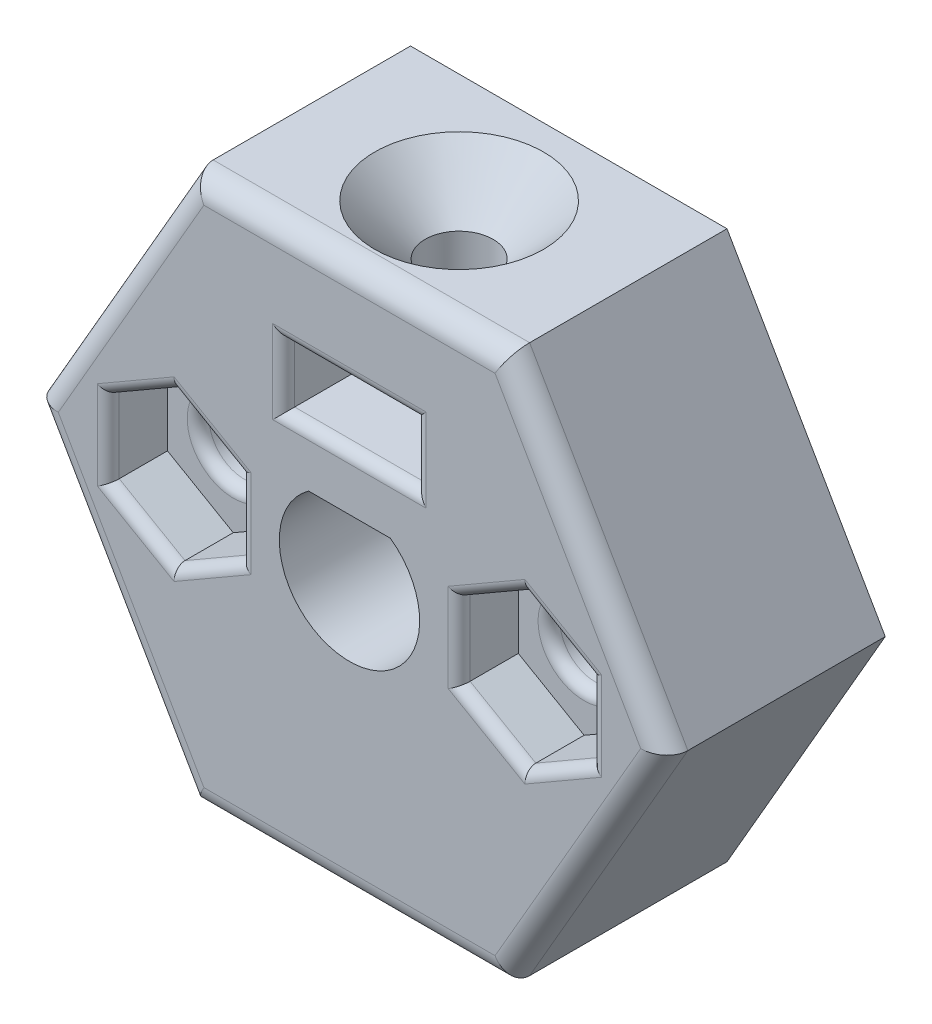
SolidWorks part; units mm, degrees
material "ABS"
ref_plane "Спереди" through (0, 0, 0) normal (0, 0, 1) x (1, 0, 0)
ref_plane "Сверху" through (0, 0, 0) normal (0, 1, 0) x (1, 0, 0)
ref_plane "Справа" through (0, 0, 0) normal (1, 0, 0) x (0, 0, -1)
sketch "Эскиз1" plane through (0, 0, 0) normal (0, 0, 1) x (1, 0, 0)
  line L1 (7.2169, -12.5) -> (14.4338, 0)
  line L2 (14.4338, 0) -> (7.2169, 12.5)
  line L3 (7.2169, 12.5) -> (-7.2169, 12.5)
  line L4 (-7.2169, 12.5) -> (-14.4338, 0)
  line L5 (-14.4338, 0) -> (-7.2169, -12.5)
  line L6 (-7.2169, -12.5) -> (7.2169, -12.5)
  circle A0 centre (0, 0) radius 12.5 construction
  dimension "D1" = 25
extrude "Бобышка-Вытянуть1" add sketch "Эскиз1" along normal blind 10
sketch "Эскиз2" plane through (0, 0, 10) normal (0, 0, 1) x (1, 0, 0)
  line L0 (-1.8, 2.4) -> (1.8, 2.4) construction
  line L1 (0, 2.4) -> (0, -3) construction
  line L2 (3, 0) -> (3.2, 0) construction
  line L3 (-1.8655, 2.6) -> (1.8655, 2.6)
  line L4 (0, 2.6) -> (0, 2.4) construction
  arc A0 (-1.8, 2.4) -> (1.8, 2.4) centre (0, 0) ccw construction
  arc A1 (-1.8655, 2.6) -> (1.8655, 2.6) centre (0, 0) ccw
  dimension "D1" = 6
  dimension "D2" = 5.4
  dimension "D3" = 0.2
extrude "Вырез-Вытянуть1" cut sketch "Эскиз2" against normal through all
sketch "Эскиз3" plane through (0, 2.6, 0) normal (0, -1, 0) x (1, 0, 0)
  line L0 (0, 5) -> (0, 0) construction
  line L3 (0, 5) -> (0, 10) construction
  line L4 (1.8655, 10) -> (-1.8655, 10) construction
  circle A0 centre (0, 5) radius 1.55
  dimension "D1" = 3.1
extrude "Вырез-Вытянуть2" cut sketch "Эскиз3" against normal up to surface (9.9 mm away) up to face at (0, 12.5, 5)
chamfer "Фаска1" distance 2.3 angle 45 1 edges at (1.55, 12.5, 5)
sketch "Эскиз4" plane through (0, 0, 10) normal (0, 0, 1) x (1, 0, 0)
  line L0 (0, 2.6) -> (0, 12.5) construction
  line L1 (1.8655, 2.6) -> (-1.8655, 2.6) construction
  line L2 (7.2169, 12.5) -> (-7.2169, 12.5) construction
  line L4 (-3, 7.9) -> (3, 7.9)
  line L5 (-3, 7.9) -> (-3, 5.1)
  line L6 (-3, 5.1) -> (3, 5.1)
  line L7 (3, 7.9) -> (3, 5.1)
  line L8 (-3, 7.9) -> (3, 5.1) construction
  line L9 (-3, 5.1) -> (3, 7.9) construction
  point P6 (0, 6.5)
  dimension "D1" = 6
  dimension "D2" = 2.8
  dimension "D3" = 2.5
extrude "Вырез-Вытянуть3" cut sketch "Эскиз4" against normal offset from surface (8.5 mm away) 1.5 up to face at (0, -0.3, 0)
fillet "Скругление1" radius 1 6 edges at (-10.8253, -6.25, 10) (0, -12.5, 10) (10.8253, -6.25, 10) (10.8253, 6.25, 10) (0, 12.5, 10) (-10.8253, 6.25, 10)
sketch "Эскиз5" plane through (0, 0, 10) normal (0, 0, 1) x (1, 0, 0)
  line L0 (0, 0) -> (-8, 0) construction
  line L1 (0, 0) -> (0, 5.1) construction
  line L2 (-11, -1.7321) -> (-8, -3.4641)
  line L3 (-8, -3.4641) -> (-5, -1.7321)
  line L4 (-5, -1.7321) -> (-5, 1.7321)
  line L5 (-5, 1.7321) -> (-8, 3.4641)
  line L6 (-8, 3.4641) -> (-11, 1.7321)
  line L7 (-11, 1.7321) -> (-11, -1.7321)
  line L8 (-3, 5.1) -> (3, 5.1) construction
  line L9 (8, -3.4641) -> (5, -1.7321)
  line L10 (11, -1.7321) -> (8, -3.4641)
  line L11 (11, 1.7321) -> (11, -1.7321)
  line L12 (8, 3.4641) -> (11, 1.7321)
  line L13 (5, 1.7321) -> (8, 3.4641)
  line L14 (5, -1.7321) -> (5, 1.7321)
  circle A0 centre (-8, 0) radius 3 construction
  dimension "D1" = 6
  dimension "D2" = 8
extrude "Вырез-Вытянуть4" cut sketch "Эскиз5" against normal blind 2.7
sketch "Эскиз6" plane through (0, 0, 7.3) normal (0, 0, 1) x (1, 0, 0)
  line L0 (-8, 0) -> (-5, 0) construction
  line L1 (-5, -1.7321) -> (-5, 1.7321) construction
  line L2 (-8, 0) -> (-11, 0) construction
  line L3 (-11, 1.7321) -> (-11, -1.7321) construction
  line L4 (0, 0) -> (0, 5.4418) construction
  circle A0 centre (-8, 0) radius 1.6
  circle A1 centre (8, 0) radius 1.6
  dimension "D1" = 3.2
extrude "Вырез-Вытянуть5" cut sketch "Эскиз6" against normal up to surface (7.3 mm away) up to face at (0, -0.3, 0)
fillet "Скругление2" radius 0.5 18 edges at (3, 6.5, 10) (0, 5.1, 10) (-3, 6.5, 10) (0, 7.9, 10) (-6.4, 0, 7.3) (6.4, 0, 7.3) (5, 0, 10) (6.5, -2.5981, 10) (9.5, -2.5981, 10) (11, 0, 10) (9.5, 2.5981, 10) (6.5, 2.5981, 10) (-9.5, -2.5981, 10) (-6.5, -2.5981, 10) (-5, 0, 10) (-6.5, 2.5981, 10) (-11, 0, 10) (-9.5, 2.5981, 10)
